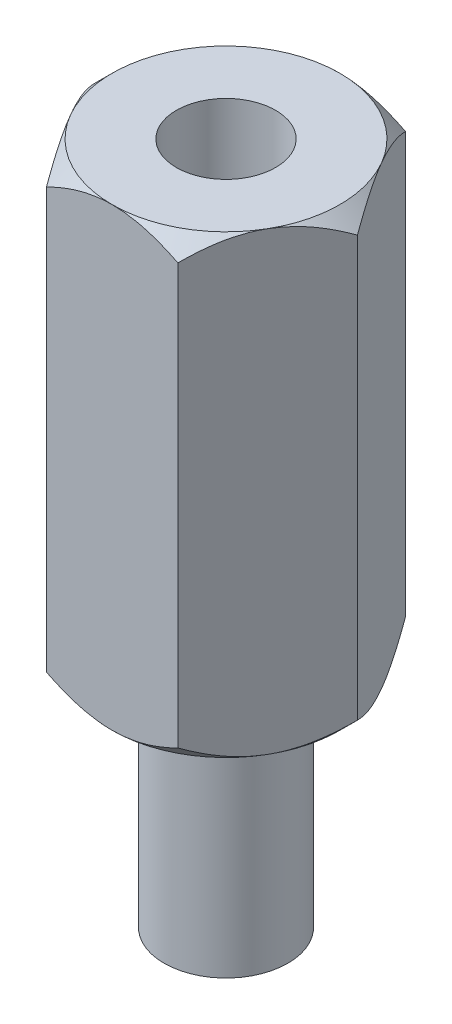
SolidWorks part; units mm, degrees
material "6061-T6 (SS)"
ref_plane "Front" through (0, 0, 0) normal (0, 0, 1) x (1, 0, 0)
ref_plane "Top" through (0, 0, 0) normal (0, 1, 0) x (1, 0, 0)
ref_plane "Right" through (0, 0, 0) normal (1, 0, 0) x (0, 0, -1)
sketch "Sketch1" plane through (0, 0, 0) normal (0, 1, 0) x (1, 0, 0)
  line L1 (3.6662, 0) -> (1.8331, 3.175)
  line L2 (1.8331, 3.175) -> (-1.8331, 3.175)
  line L3 (-1.8331, 3.175) -> (-3.6662, 0)
  line L4 (-3.6662, 0) -> (-1.8331, -3.175)
  line L5 (-1.8331, -3.175) -> (1.8331, -3.175)
  line L6 (1.8331, -3.175) -> (3.6662, 0)
  circle A0 centre (0, 0) radius 3.175 construction
extrude "Boss-Extrude1" add sketch "Sketch1" along normal blind 12.7
sketch "Sketch2" plane through (0, 0, 0) normal (0, 0, 1) x (1, 0, 0)
  line L0 (-3.6662, 0.4912) -> (-3.175, 0)
  line L1 (-3.175, 0) -> (-3.6662, 0)
  line L2 (-3.6662, 0) -> (-3.6662, 0.4912)
  line L5 (-3.6662, 12.7) -> (-3.6662, 0) construction
  line L6 (0, 0) -> (0, 2.0631) construction
  line L7 (-3.6662, 12.7) -> (-3.6662, 12.2088)
  line L8 (-3.6662, 12.2088) -> (-3.175, 12.7)
  line L9 (-3.6662, 12.7) -> (-1.8331, 12.7) construction
  line L10 (-3.175, 12.7) -> (-3.6662, 12.7)
revolve "Cut-Revolve1" cut sketch "Sketch2" angle 360 about L6
sketch "Sketch5" plane through (0, 12.7, 0) normal (0, 1, 0) x (1, 0, 0)
  circle A0 centre (0, 0) radius 1.3843
extrude "Cut-Extrude1" cut sketch "Sketch5" against normal blind 6.35
sketch "Sketch6" plane through (0, 0, 0) normal (0, -1, 0) x (1, 0, 0)
  circle A0 centre (0, 0) radius 1.7272
extrude "Boss-Extrude2" add sketch "Sketch6" along normal blind 6.35
